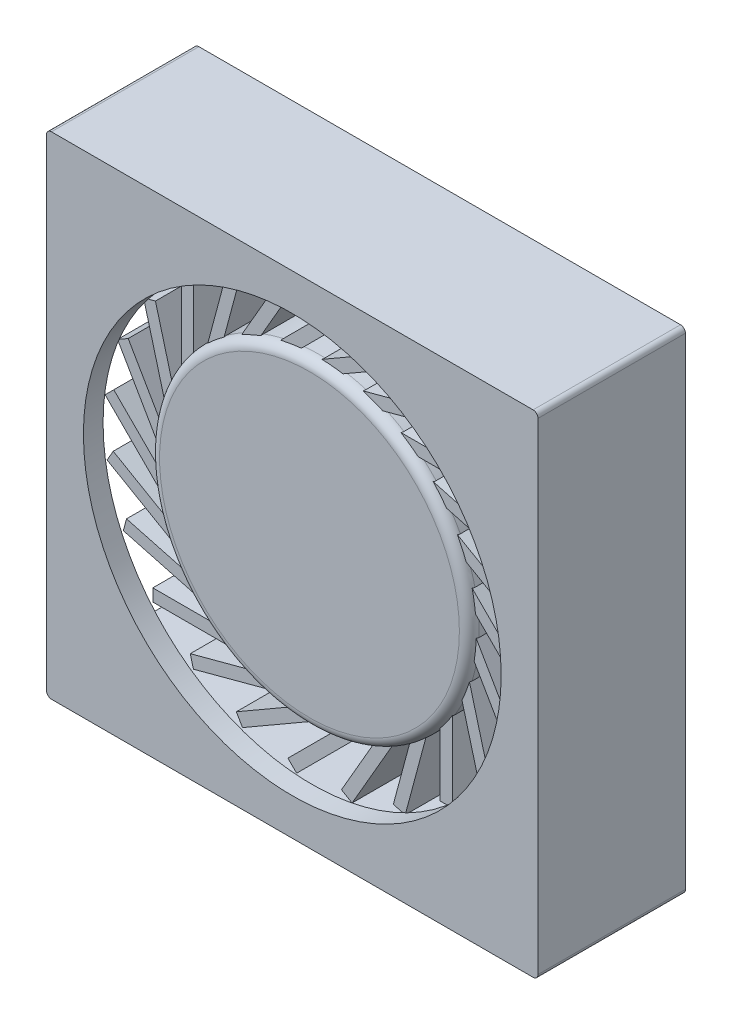
SolidWorks part; units mm, degrees
ref_plane "前视基准面" through (0, 0, 0) normal (0, 0, 1) x (1, 0, 0)
ref_plane "上视基准面" through (0, 0, 0) normal (0, 1, 0) x (1, 0, 0)
ref_plane "右视基准面" through (0, 0, 0) normal (1, 0, 0) x (0, 0, -1)
sketch "草图1" plane through (0, 0, 0) normal (0, 0, 1) x (1, 0, 0)
  line L1 (0, 0) -> (20, 0)
  line L2 (0, 0) -> (0, -20)
  line L3 (0, -20) -> (20, -20)
  line L4 (20, 0) -> (20, -20)
extrude "凸台-拉伸1" add sketch "草图1" along normal blind 6
shell "抽壳1" thickness 0.8
sketch "草图2" plane through (0, 0, 6) normal (0, 0, 1) x (1, 0, 0)
  line L0 (0, 0) -> (20, -20) construction
  circle A0 centre (10, -10) radius 8.5
extrude "切除-拉伸1" cut sketch "草图2" against normal blind 5
sketch "草图3" plane through (0, 0, 0.8) normal (0, 0, 1) x (1, 0, 0)
  circle A0 centre (10, -10) radius 6.5
extrude "凸台-拉伸2" add sketch "草图3" along normal blind 4.5
fillet "圆角1" radius 0.4 1 edges at (16.5, -10, 5.3)
sketch "草图4" plane through (0, 0, 0.8) normal (0, 0, 1) x (1, 0, 0)
  line L0 (3.7826, -10.2539) -> (1.8891, -6.9743)
  line L1 (1.8891, -6.9743) -> (2.3221, -6.7243)
  line L2 (2.3221, -6.7243) -> (4.2156, -10.0039)
  line L3 (4.2156, -10.0039) -> (3.7826, -10.2539)
  line L4 (4.4117, -8.5067) -> (3.9287, -8.6361)
  line L5 (3.9287, -8.6361) -> (2.9486, -4.9781)
  line L6 (2.9486, -4.9781) -> (3.4315, -4.8487)
  line L7 (3.4315, -4.8487) -> (4.4117, -8.5067)
  line L8 (4.9886, -7.1112) -> (4.4886, -7.1112)
  line L9 (4.4886, -7.1112) -> (4.4886, -3.3242)
  line L10 (4.4886, -3.3242) -> (4.9886, -3.3242)
  line L11 (4.9886, -3.3242) -> (4.9886, -7.1112)
  line L12 (5.907, -5.9126) -> (5.4241, -5.7832)
  line L13 (5.4241, -5.7832) -> (6.4042, -2.1252)
  line L14 (6.4042, -2.1252) -> (6.8872, -2.2546)
  line L15 (6.8872, -2.2546) -> (5.907, -5.9126)
  line L16 (7.1044, -4.9925) -> (6.6714, -4.7425)
  line L17 (6.6714, -4.7425) -> (8.5649, -1.4629)
  line L18 (8.5649, -1.4629) -> (8.9979, -1.7129)
  line L19 (8.9979, -1.7129) -> (7.1044, -4.9925)
  line L20 (8.4991, -4.4137) -> (8.1455, -4.0602)
  line L21 (8.1455, -4.0602) -> (10.8234, -1.3823)
  line L22 (10.8234, -1.3823) -> (11.1769, -1.7359)
  line L23 (11.1769, -1.7359) -> (8.4991, -4.4137)
  line L24 (9.9961, -4.2156) -> (9.7461, -3.7826)
  line L25 (9.7461, -3.7826) -> (13.0257, -1.8891)
  line L26 (13.0257, -1.8891) -> (13.2757, -2.3221)
  line L27 (13.2757, -2.3221) -> (9.9961, -4.2156)
  line L28 (11.4933, -4.4117) -> (11.3639, -3.9287)
  line L29 (11.3639, -3.9287) -> (15.0219, -2.9486)
  line L30 (15.0219, -2.9486) -> (15.1513, -3.4315)
  line L31 (15.1513, -3.4315) -> (11.4933, -4.4117)
  line L32 (12.8888, -4.9886) -> (12.8888, -4.4886)
  line L33 (12.8888, -4.4886) -> (16.6758, -4.4886)
  line L34 (16.6758, -4.4886) -> (16.6758, -4.9886)
  line L35 (16.6758, -4.9886) -> (12.8888, -4.9886)
  line L36 (14.0874, -5.907) -> (14.2168, -5.4241)
  line L37 (14.2168, -5.4241) -> (17.8748, -6.4042)
  line L38 (17.8748, -6.4042) -> (17.7454, -6.8872)
  line L39 (17.7454, -6.8872) -> (14.0874, -5.907)
  line L40 (15.0075, -7.1044) -> (15.2575, -6.6714)
  line L41 (15.2575, -6.6714) -> (18.5371, -8.5649)
  line L42 (18.5371, -8.5649) -> (18.2871, -8.9979)
  line L43 (18.2871, -8.9979) -> (15.0075, -7.1044)
  line L44 (15.5863, -8.4991) -> (15.9398, -8.1455)
  line L45 (15.9398, -8.1455) -> (18.6177, -10.8234)
  line L46 (18.6177, -10.8234) -> (18.2641, -11.1769)
  line L47 (18.2641, -11.1769) -> (15.5863, -8.4991)
  line L48 (15.7844, -9.9961) -> (16.2174, -9.7461)
  line L49 (16.2174, -9.7461) -> (18.1109, -13.0257)
  line L50 (18.1109, -13.0257) -> (17.6779, -13.2757)
  line L51 (17.6779, -13.2757) -> (15.7844, -9.9961)
  line L52 (15.5883, -11.4933) -> (16.0713, -11.3639)
  line L53 (16.0713, -11.3639) -> (17.0514, -15.0219)
  line L54 (17.0514, -15.0219) -> (16.5685, -15.1513)
  line L55 (16.5685, -15.1513) -> (15.5883, -11.4933)
  line L56 (15.0114, -12.8888) -> (15.5114, -12.8888)
  line L57 (15.5114, -12.8888) -> (15.5114, -16.6758)
  line L58 (15.5114, -16.6758) -> (15.0114, -16.6758)
  line L59 (15.0114, -16.6758) -> (15.0114, -12.8888)
  line L60 (14.093, -14.0874) -> (14.5759, -14.2168)
  line L61 (14.5759, -14.2168) -> (13.5958, -17.8748)
  line L62 (13.5958, -17.8748) -> (13.1128, -17.7454)
  line L63 (13.1128, -17.7454) -> (14.093, -14.0874)
  line L64 (12.8956, -15.0075) -> (13.3286, -15.2575)
  line L65 (13.3286, -15.2575) -> (11.4351, -18.5371)
  line L66 (11.4351, -18.5371) -> (11.0021, -18.2871)
  line L67 (11.0021, -18.2871) -> (12.8956, -15.0075)
  line L68 (11.5009, -15.5863) -> (11.8545, -15.9398)
  line L69 (11.8545, -15.9398) -> (9.1766, -18.6177)
  line L70 (9.1766, -18.6177) -> (8.8231, -18.2641)
  line L71 (8.8231, -18.2641) -> (11.5009, -15.5863)
  line L72 (10.0039, -15.7844) -> (10.2539, -16.2174)
  line L73 (10.2539, -16.2174) -> (6.9743, -18.1109)
  line L74 (6.9743, -18.1109) -> (6.7243, -17.6779)
  line L75 (6.7243, -17.6779) -> (10.0039, -15.7844)
  line L76 (8.5067, -15.5883) -> (8.6361, -16.0713)
  line L77 (8.6361, -16.0713) -> (4.9781, -17.0514)
  line L78 (4.9781, -17.0514) -> (4.8487, -16.5685)
  line L79 (4.8487, -16.5685) -> (8.5067, -15.5883)
  line L80 (7.1112, -15.0114) -> (7.1112, -15.5114)
  line L81 (7.1112, -15.5114) -> (3.3242, -15.5114)
  line L82 (3.3242, -15.5114) -> (3.3242, -15.0114)
  line L83 (3.3242, -15.0114) -> (7.1112, -15.0114)
  line L84 (5.9126, -14.093) -> (5.7832, -14.5759)
  line L85 (5.7832, -14.5759) -> (2.1252, -13.5958)
  line L86 (2.1252, -13.5958) -> (2.2546, -13.1128)
  line L87 (2.2546, -13.1128) -> (5.9126, -14.093)
  line L88 (4.9925, -12.8956) -> (4.7425, -13.3286)
  line L89 (4.7425, -13.3286) -> (1.4629, -11.4351)
  line L90 (1.4629, -11.4351) -> (1.7129, -11.0021)
  line L91 (1.7129, -11.0021) -> (4.9925, -12.8956)
  line L92 (4.4137, -11.5009) -> (4.0602, -11.8545)
  line L93 (4.0602, -11.8545) -> (1.3823, -9.1766)
  line L94 (1.3823, -9.1766) -> (1.7359, -8.8231)
  line L95 (1.7359, -8.8231) -> (4.4137, -11.5009)
  point P4 (10, -10)
  dimension "D1" = 24
extrude "凸台-拉伸4" add sketch "草图4" along normal blind 4.2
fillet "圆角2" radius 0.2 4 edges at (20, 0, 3) (0, 0, 3) (20, -20, 3) (0, -20, 3)
